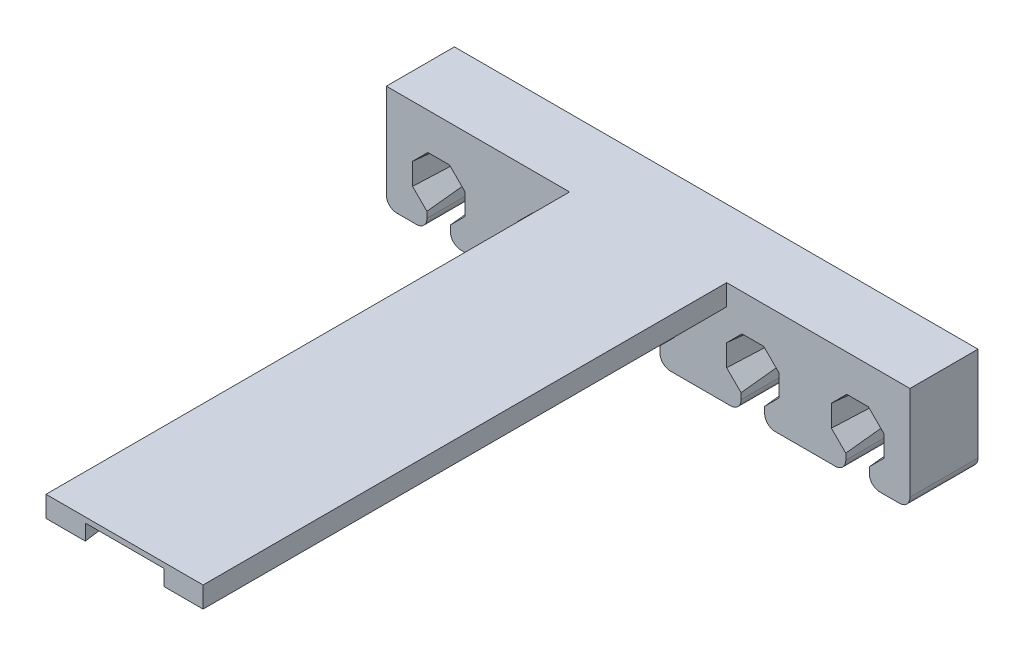
SolidWorks part; units mm, degrees
ref_plane "Front Plane" through (0, 0, 0) normal (0, 0, 1) x (1, 0, 0)
ref_plane "Top Plane" through (0, 0, 0) normal (0, 1, 0) x (1, 0, 0)
ref_plane "Right Plane" through (0, 0, 0) normal (1, 0, 0) x (0, 0, -1)
sketch "Sketch1" plane through (0, 0, 0) normal (0, 0, 1) x (1, 0, 0)
  line L1 (0, 0) -> (100, 0)
  line L2 (0, 0) -> (0, 20)
  line L3 (0, 20) -> (100, 20)
  line L4 (100, 0) -> (100, 20)
  dimension "D1" = 100
  dimension "D2" = 20
extrude "Boss-Extrude1" add sketch "Sketch1" along normal blind 13
sketch "Sketch2" plane through (0, 0, 13) normal (0, 0, 1) x (1, 0, 0)
  line L0 (0, 8) -> (100, 8) construction
  line L1 (100, 0) -> (100, 20) construction
  line L2 (10, 20) -> (10, 0) construction
  line L3 (50, 20) -> (50, 0) construction
  line L4 (100, 20) -> (0, 20) construction
  line L5 (0, 0) -> (100, 0) construction
  line L6 (30, 20) -> (30, 0) construction
  line L10 (70, 20) -> (70, 0) construction
  line L11 (90, 20) -> (90, 0) construction
  line L31 (15, 5.9289) -> (15, 10.0711)
  line L32 (15, 10.0711) -> (12.0711, 13)
  line L33 (12.0711, 13) -> (7.9289, 13)
  line L34 (7.9289, 13) -> (5, 10.0711)
  line L35 (5, 10.0711) -> (5, 5.9289)
  line L36 (5, 5.9289) -> (7.9289, 3)
  line L37 (7.9289, 3) -> (12.0711, 3)
  line L38 (12.0711, 3) -> (15, 5.9289)
  line L39 (35, 5.9289) -> (35, 10.0711)
  line L40 (35, 10.0711) -> (32.0711, 13)
  line L41 (32.0711, 13) -> (27.9289, 13)
  line L42 (27.9289, 13) -> (25, 10.0711)
  line L43 (25, 10.0711) -> (25, 5.9289)
  line L44 (25, 5.9289) -> (27.9289, 3)
  line L45 (27.9289, 3) -> (32.0711, 3)
  line L46 (32.0711, 3) -> (35, 5.9289)
  line L47 (52.0711, 3) -> (55, 5.9289)
  line L48 (55, 5.9289) -> (55, 10.0711)
  line L49 (55, 10.0711) -> (52.0711, 13)
  line L50 (52.0711, 13) -> (47.9289, 13)
  line L51 (47.9289, 13) -> (45, 10.0711)
  line L52 (45, 10.0711) -> (45, 5.9289)
  line L53 (45, 5.9289) -> (47.9289, 3)
  line L54 (47.9289, 3) -> (52.0711, 3)
  line L55 (75, 5.9289) -> (75, 10.0711)
  line L56 (75, 10.0711) -> (72.0711, 13)
  line L57 (72.0711, 13) -> (67.9289, 13)
  line L58 (67.9289, 13) -> (65, 10.0711)
  line L59 (65, 10.0711) -> (65, 5.9289)
  line L60 (65, 5.9289) -> (67.9289, 3)
  line L61 (67.9289, 3) -> (72.0711, 3)
  line L62 (72.0711, 3) -> (75, 5.9289)
  line L63 (95, 5.9289) -> (95, 10.0711)
  line L64 (95, 10.0711) -> (92.0711, 13)
  line L65 (92.0711, 13) -> (87.9289, 13)
  line L66 (87.9289, 13) -> (85, 10.0711)
  line L67 (85, 10.0711) -> (85, 5.9289)
  line L68 (85, 5.9289) -> (87.9289, 3)
  line L69 (87.9289, 3) -> (92.0711, 3)
  line L70 (92.0711, 3) -> (95, 5.9289)
  circle A2 centre (10, 8) radius 5 construction
  circle A3 centre (30, 8) radius 5 construction
  circle A4 centre (50, 8) radius 5 construction
  circle A5 centre (70, 8) radius 5 construction
  circle A6 centre (90, 8) radius 5 construction
  dimension "D1" = 20
  dimension "D2" = 20
  dimension "D3" = 8
  dimension "D5" = 20
  dimension "D6" = 20
  dimension "D11" = 10
  dimension "D12" = 10
  dimension "D13" = 10
  dimension "D14" = 10
  dimension "D15" = 10
extrude "Cut-Extrude1" cut sketch "Sketch2" against normal through all draft 4.5
sketch "Sketch3" plane through (0, 0, 13) normal (0, 0, 1) x (1, 0, 0)
  line L0 (0, 0) -> (100, 0) construction
  line L1 (30, 3) -> (30, 13) construction
  line L2 (27.9289, 3) -> (32.0711, 3) construction
  line L3 (32.0711, 13) -> (27.9289, 13) construction
  line L5 (10, 3) -> (10, 13) construction
  line L6 (0, 10) -> (100, 10) construction
  line L12 (0, 20) -> (0, 0) construction
  line L13 (100, 0) -> (100, 20) construction
  line L19 (7.75, 0) -> (12.25, 0)
  line L20 (7.75, 0) -> (7.75, 10)
  line L21 (7.75, 10) -> (12.25, 10)
  line L22 (12.25, 0) -> (12.25, 10)
  line L23 (27.75, 0) -> (32.25, 0)
  line L24 (27.75, 0) -> (27.75, 10)
  line L25 (27.75, 10) -> (32.25, 10)
  line L26 (32.25, 0) -> (32.25, 10)
  line L27 (47.75, 0) -> (52.25, 0)
  line L28 (47.75, 0) -> (47.75, 10)
  line L29 (47.75, 10) -> (52.25, 10)
  line L30 (52.25, 0) -> (52.25, 10)
  line L31 (67.75, 0) -> (72.25, 0)
  line L32 (67.75, 0) -> (67.75, 10)
  line L33 (67.75, 10) -> (72.25, 10)
  line L34 (72.25, 0) -> (72.25, 10)
  line L35 (87.75, 0) -> (92.25, 0)
  line L36 (87.75, 0) -> (87.75, 10)
  line L37 (87.75, 10) -> (92.25, 10)
  line L38 (92.25, 0) -> (92.25, 10)
  line L52 (90, 13) -> (90, 3) construction
  line L53 (92.0711, 13) -> (87.9289, 13) construction
  line L54 (87.9289, 3) -> (92.0711, 3) construction
  line L55 (70, 13) -> (70, 3) construction
  line L56 (72.0711, 13) -> (67.9289, 13) construction
  line L57 (67.9289, 3) -> (72.0711, 3) construction
  line L58 (50, 13) -> (50, 3) construction
  line L59 (52.0711, 13) -> (47.9289, 13) construction
  line L60 (47.9289, 3) -> (52.0711, 3) construction
  line L64 (10, 13) -> (10, 3) construction
  line L65 (12.0711, 13) -> (7.9289, 13) construction
  line L66 (7.9289, 3) -> (12.0711, 3) construction
  dimension "D1" = 4.5
  dimension "D2" = 2.25
  dimension "D4" = 2.25
  dimension "D6" = 2.25
  dimension "D7" = 2.25
  dimension "D8" = 2.25
extrude "Cut-Extrude2" cut sketch "Sketch3" against normal through all
sketch "Sketch4" plane through (0, 0, 13) normal (0, 0, 1) x (1, 0, 0)
  line L0 (100, 20) -> (0, 20) construction
  line L1 (35, 20) -> (65, 20)
  line L2 (35, 20) -> (35, 16)
  line L3 (35, 16) -> (65, 16)
  line L4 (65, 20) -> (65, 16)
  line L5 (50, 13) -> (50, 20) construction
  line L6 (52.0711, 13) -> (47.9289, 13) construction
  dimension "D1" = 30
  dimension "D2" = 4
  dimension "D3" = 15
extrude "Boss-Extrude2" add sketch "Sketch4" along normal blind 100
sketch "Sketch5" plane through (0, 16, 0) normal (0, -1, 0) x (1, 0, 0)
  line L0 (42.5, 113) -> (40, 93)
  line L1 (35, 113) -> (65, 113) construction
  line L2 (40, 93) -> (60, 93)
  line L3 (60, 93) -> (57.5, 113)
  line L4 (57.5, 113) -> (42.5, 113)
  line L5 (35, 113) -> (35, 13) construction
  dimension "D1" = 20
  dimension "D2" = 20
  dimension "D3" = 5
  dimension "D4" = 15
  dimension "D5" = 7.5
extrude "Cut-Extrude3" cut sketch "Sketch5" against normal offset from surface (3 mm away) 1 up to face at (50, 20, 34.75)
fillet "Fillet1" radius 2 12 edges at (0, 0, 6.5) (100, 0, 6.5) (92.25, 0, 6.5) (87.75, 0, 6.5) (72.25, 0, 6.5) (67.75, 0, 6.5) (52.25, 0, 6.5) (47.75, 0, 6.5) (32.25, 0, 6.5) (27.75, 0, 6.5) (12.25, 0, 6.5) (7.75, 0, 6.5)
